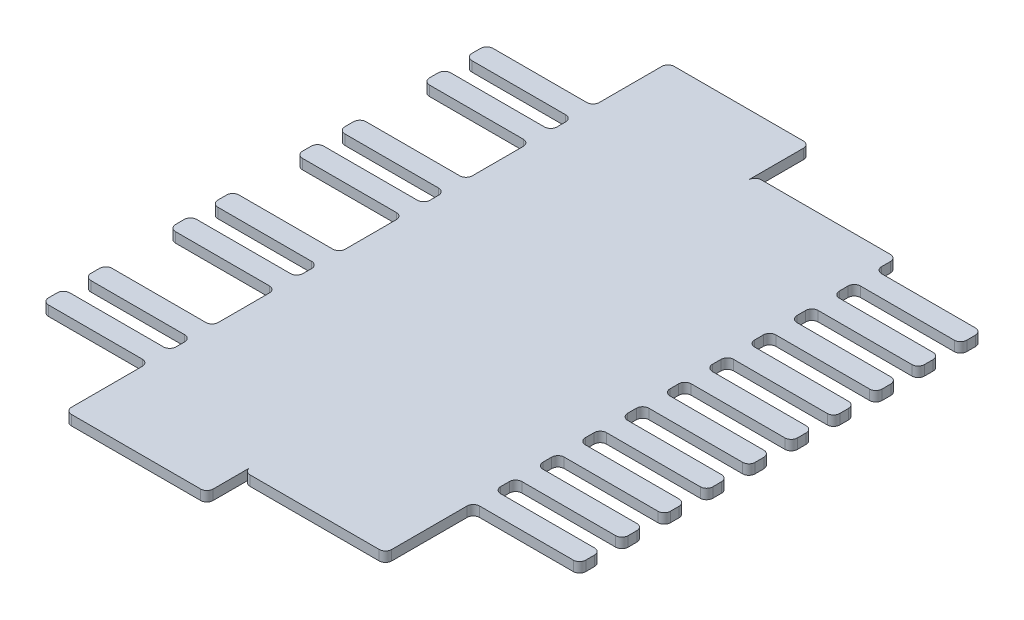
SolidWorks part; units mm, degrees
ref_plane "Front Plane" through (0, 0, 0) normal (0, 0, 1) x (1, 0, 0)
ref_plane "Top Plane" through (0, 0, 0) normal (0, 1, 0) x (1, 0, 0)
ref_plane "Right Plane" through (0, 0, 0) normal (1, 0, 0) x (0, 0, -1)
sketch "Sketch1" plane through (0, 0, 0) normal (0, 1, 0) x (1, 0, 0)
  line L0 (-0.75, 10) -> (-12, 10)
  line L2 (0, 9.25) -> (0, 0.75)
  line L5 (-12.75, 11.27) -> (0, 11.27) construction
  line L7 (-12.75, 10.75) -> (-12.75, 11.79)
  line L8 (-12, 12.54) -> (-0.75, 12.54)
  line L12 (0, 14.33) -> (0, 13.29)
  line L17 (-0.75, 15.08) -> (-12, 15.08)
  line L22 (-12.75, 15.83) -> (-12.75, 16.87)
  line L27 (-12, 17.62) -> (-0.75, 17.62)
  line L56 (16.25, 0) -> (0.75, 0)
  line L84 (0, 19.41) -> (0, 10.91) [skipped]
  line L85 (-0.75, 20.16) -> (-12, 20.16) [skipped]
  line L86 (-12.75, 20.91) -> (-12.75, 21.95) [skipped]
  line L87 (-12, 22.7) -> (-0.75, 22.7) [skipped]
  line L88 (0, 24.49) -> (0, 15.99) [skipped]
  line L89 (-0.75, 25.24) -> (-12, 25.24) [skipped]
  line L90 (-12.75, 25.99) -> (-12.75, 27.03) [skipped]
  line L91 (-12, 27.78) -> (-0.75, 27.78) [skipped]
  line L92 (0, 29.57) -> (0, 21.07) [skipped]
  line L93 (-0.75, 30.32) -> (-12, 30.32) [skipped]
  line L94 (-12.75, 31.07) -> (-12.75, 32.11) [skipped]
  line L95 (-12, 32.86) -> (-0.75, 32.86) [skipped]
  line L96 (0, 34.65) -> (0, 26.15) [skipped]
  line L97 (-0.75, 35.4) -> (-12, 35.4) [skipped]
  line L98 (-12.75, 36.15) -> (-12.75, 37.19) [skipped]
  line L99 (-12, 37.94) -> (-0.75, 37.94) [skipped]
  line L100 (0, 39.73) -> (0, 31.23) [skipped]
  line L101 (-0.75, 40.48) -> (-12, 40.48) [skipped]
  line L102 (-12.75, 41.23) -> (-12.75, 42.27) [skipped]
  line L103 (-12, 43.02) -> (-0.75, 43.02) [skipped]
  line L104 (0, 44.81) -> (0, 36.31) [skipped]
  line L105 (-0.75, 45.56) -> (-12, 45.56) [skipped]
  line L106 (-12.75, 46.31) -> (-12.75, 47.35) [skipped]
  line L107 (-12, 48.1) -> (-0.75, 48.1) [skipped]
  line L108 (0, 49.89) -> (0, 41.39) [skipped]
  line L109 (-0.75, 50.64) -> (-12, 50.64) [skipped]
  line L110 (-12.75, 51.39) -> (-12.75, 52.43) [skipped]
  line L111 (-12, 53.18) -> (-0.75, 53.18) [skipped]
  line L112 (0, 54.97) -> (0, 46.47) [skipped]
  line L113 (-0.75, 55.72) -> (-12, 55.72) [skipped]
  line L114 (-12.75, 56.47) -> (-12.75, 57.51) [skipped]
  line L115 (-12, 58.26) -> (-0.75, 58.26) [skipped]
  line L116 (-0.75, 25.24) -> (-12, 25.24)
  line L117 (-12.75, 25.99) -> (-12.75, 27.03)
  line L118 (-12, 27.78) -> (-0.75, 27.78)
  line L119 (0, 29.57) -> (0, 28.53)
  line L120 (-0.75, 30.32) -> (-12, 30.32)
  line L121 (-12.75, 31.07) -> (-12.75, 32.11)
  line L122 (-12, 32.86) -> (-0.75, 32.86)
  line L123 (-0.75, 40.48) -> (-12, 40.48)
  line L124 (-12.75, 41.23) -> (-12.75, 42.27)
  line L125 (-12, 43.02) -> (-0.75, 43.02)
  line L126 (0, 44.81) -> (0, 43.77)
  line L127 (-0.75, 45.56) -> (-12, 45.56)
  line L128 (-12.75, 46.31) -> (-12.75, 47.35)
  line L129 (-12, 48.1) -> (-0.75, 48.1)
  line L130 (-0.75, 55.72) -> (-12, 55.72)
  line L131 (-12.75, 56.47) -> (-12.75, 57.51)
  line L132 (-12, 58.26) -> (-0.75, 58.26)
  line L133 (0, 60.05) -> (0, 59.01)
  line L134 (-0.75, 60.8) -> (-12, 60.8)
  line L135 (-12.75, 61.55) -> (-12.75, 62.59)
  line L136 (-12, 63.34) -> (-0.75, 63.34)
  line L137 (0, 24.49) -> (0, 18.37)
  line L138 (0, 33.61) -> (0, 39.73)
  line L139 (0, 48.85) -> (0, 54.97)
  line L140 (0, 64.09) -> (0, 71.59)
  line L141 (0.75, 72.34) -> (16.25, 72.34)
  line L142 (17, 71.59) -> (17, 65.023)
  line L143 (34.75, 63.233) -> (46, 63.233)
  line L144 (34, 63.983) -> (34, 65.023)
  line L145 (46.75, 61.963) -> (34, 61.963) construction
  line L146 (46.75, 62.483) -> (46.75, 61.443)
  line L147 (46, 60.693) -> (34.75, 60.693)
  line L148 (34, 58.903) -> (34, 59.943)
  line L149 (34.75, 58.153) -> (46, 58.153)
  line L150 (46.75, 57.403) -> (46.75, 56.363)
  line L151 (46, 55.613) -> (34.75, 55.613)
  line L152 (34, 53.823) -> (34, 54.863)
  line L153 (34.75, 53.073) -> (46, 53.073)
  line L154 (46.75, 52.323) -> (46.75, 51.283)
  line L155 (46, 50.533) -> (34.75, 50.533)
  line L156 (34, 48.743) -> (34, 49.783)
  line L157 (34, 14.223) -> (34, 5.183)
  line L158 (33.25, 4.433) -> (17.75, 4.433)
  line L159 (17, 5.183) -> (17, 65.023) construction
  line L160 (17.75, 65.773) -> (33.25, 65.773)
  line L161 (34.75, 47.993) -> (46, 47.993)
  line L162 (46.75, 47.243) -> (46.75, 46.203)
  line L163 (46, 45.453) -> (34.75, 45.453)
  line L164 (34, 43.663) -> (34, 44.703)
  line L165 (34.75, 42.913) -> (46, 42.913)
  line L166 (46.75, 42.163) -> (46.75, 41.123)
  line L167 (46, 40.373) -> (34.75, 40.373)
  line L168 (34, 38.583) -> (34, 39.623)
  line L169 (34.75, 37.833) -> (46, 37.833)
  line L170 (46.75, 37.083) -> (46.75, 36.043)
  line L171 (46, 35.293) -> (34.75, 35.293)
  line L172 (34, 33.503) -> (34, 34.543)
  line L173 (34.75, 32.753) -> (46, 32.753)
  line L174 (46.75, 32.003) -> (46.75, 30.963)
  line L175 (46, 30.213) -> (34.75, 30.213)
  line L176 (34, 28.423) -> (34, 29.463)
  line L177 (34.75, 27.673) -> (46, 27.673)
  line L178 (46.75, 26.923) -> (46.75, 25.883)
  line L179 (46, 25.133) -> (34.75, 25.133)
  line L180 (34, 23.343) -> (34, 24.383)
  line L181 (34.75, 22.593) -> (46, 22.593)
  line L182 (46.75, 21.843) -> (46.75, 20.803)
  line L183 (46, 20.053) -> (34.75, 20.053)
  line L184 (34, 18.263) -> (34, 19.303)
  line L185 (34.75, 17.513) -> (46, 17.513)
  line L186 (46.75, 16.763) -> (46.75, 15.723)
  line L187 (46, 14.973) -> (34.75, 14.973)
  line L188 (17, 65.023) -> (17, 5.183) construction
  line L189 (17, 5.183) -> (17, 0.75)
  arc A0 (-0.75, 12.54) -> (0, 13.29) centre (-0.75, 13.29) ccw
  arc A1 (-12.75, 11.79) -> (-12, 12.54) centre (-12, 11.79) cw
  arc A2 (-12, 10) -> (-12.75, 10.75) centre (-12, 10.75) cw
  arc A3 (0, 0.75) -> (0.75, 0) centre (0.75, 0.75) ccw
  arc A4 (-0.75, 10) -> (0, 9.25) centre (-0.75, 9.25) cw
  arc A5 (17, 0.75) -> (16.25, 0) centre (16.25, 0.75) cw
  arc A6 (-0.75, 15.08) -> (0, 14.33) centre (-0.75, 14.33) cw
  arc A7 (-12, 15.08) -> (-12.75, 15.83) centre (-12, 15.83) cw
  arc A8 (-12.75, 16.87) -> (-12, 17.62) centre (-12, 16.87) cw
  arc A9 (-0.75, 17.62) -> (0, 18.37) centre (-0.75, 18.37) ccw
  arc A44 (-0.75, 20.16) -> (0, 19.41) centre (-0.75, 19.41) cw [skipped]
  arc A45 (-12, 20.16) -> (-12.75, 20.91) centre (-12, 20.91) cw [skipped]
  arc A46 (-12.75, 21.95) -> (-12, 22.7) centre (-12, 21.95) cw [skipped]
  arc A47 (-0.75, 22.7) -> (0, 23.45) centre (-0.75, 23.45) ccw [skipped]
  arc A48 (-0.75, 25.24) -> (0, 24.49) centre (-0.75, 24.49) cw [skipped]
  arc A49 (-12, 25.24) -> (-12.75, 25.99) centre (-12, 25.99) cw [skipped]
  arc A50 (-12.75, 27.03) -> (-12, 27.78) centre (-12, 27.03) cw [skipped]
  arc A51 (-0.75, 27.78) -> (0, 28.53) centre (-0.75, 28.53) ccw [skipped]
  arc A52 (-0.75, 30.32) -> (0, 29.57) centre (-0.75, 29.57) cw [skipped]
  arc A53 (-12, 30.32) -> (-12.75, 31.07) centre (-12, 31.07) cw [skipped]
  arc A54 (-12.75, 32.11) -> (-12, 32.86) centre (-12, 32.11) cw [skipped]
  arc A55 (-0.75, 32.86) -> (0, 33.61) centre (-0.75, 33.61) ccw [skipped]
  arc A56 (-0.75, 35.4) -> (0, 34.65) centre (-0.75, 34.65) cw [skipped]
  arc A57 (-12, 35.4) -> (-12.75, 36.15) centre (-12, 36.15) cw [skipped]
  arc A58 (-12.75, 37.19) -> (-12, 37.94) centre (-12, 37.19) cw [skipped]
  arc A59 (-0.75, 37.94) -> (0, 38.69) centre (-0.75, 38.69) ccw [skipped]
  arc A60 (-0.75, 40.48) -> (0, 39.73) centre (-0.75, 39.73) cw [skipped]
  arc A61 (-12, 40.48) -> (-12.75, 41.23) centre (-12, 41.23) cw [skipped]
  arc A62 (-12.75, 42.27) -> (-12, 43.02) centre (-12, 42.27) cw [skipped]
  arc A63 (-0.75, 43.02) -> (0, 43.77) centre (-0.75, 43.77) ccw [skipped]
  arc A64 (-0.75, 45.56) -> (0, 44.81) centre (-0.75, 44.81) cw [skipped]
  arc A65 (-12, 45.56) -> (-12.75, 46.31) centre (-12, 46.31) cw [skipped]
  arc A66 (-12.75, 47.35) -> (-12, 48.1) centre (-12, 47.35) cw [skipped]
  arc A67 (-0.75, 48.1) -> (0, 48.85) centre (-0.75, 48.85) ccw [skipped]
  arc A68 (-0.75, 50.64) -> (0, 49.89) centre (-0.75, 49.89) cw [skipped]
  arc A69 (-12, 50.64) -> (-12.75, 51.39) centre (-12, 51.39) cw [skipped]
  arc A70 (-12.75, 52.43) -> (-12, 53.18) centre (-12, 52.43) cw [skipped]
  arc A71 (-0.75, 53.18) -> (0, 53.93) centre (-0.75, 53.93) ccw [skipped]
  arc A72 (-0.75, 55.72) -> (0, 54.97) centre (-0.75, 54.97) cw [skipped]
  arc A73 (-12, 55.72) -> (-12.75, 56.47) centre (-12, 56.47) cw [skipped]
  arc A74 (-12.75, 57.51) -> (-12, 58.26) centre (-12, 57.51) cw [skipped]
  arc A75 (-0.75, 58.26) -> (0, 59.01) centre (-0.75, 59.01) ccw [skipped]
  arc A76 (-0.75, 27.78) -> (0, 28.53) centre (-0.75, 28.53) ccw
  arc A77 (-12.75, 27.03) -> (-12, 27.78) centre (-12, 27.03) cw
  arc A78 (-12, 25.24) -> (-12.75, 25.99) centre (-12, 25.99) cw
  arc A79 (-0.75, 25.24) -> (0, 24.49) centre (-0.75, 24.49) cw
  arc A80 (-0.75, 30.32) -> (0, 29.57) centre (-0.75, 29.57) cw
  arc A81 (-12, 30.32) -> (-12.75, 31.07) centre (-12, 31.07) cw
  arc A82 (-12.75, 32.11) -> (-12, 32.86) centre (-12, 32.11) cw
  arc A83 (-0.75, 32.86) -> (0, 33.61) centre (-0.75, 33.61) ccw
  arc A84 (-0.75, 43.02) -> (0, 43.77) centre (-0.75, 43.77) ccw
  arc A85 (-12.75, 42.27) -> (-12, 43.02) centre (-12, 42.27) cw
  arc A86 (-12, 40.48) -> (-12.75, 41.23) centre (-12, 41.23) cw
  arc A87 (-0.75, 40.48) -> (0, 39.73) centre (-0.75, 39.73) cw
  arc A88 (-0.75, 45.56) -> (0, 44.81) centre (-0.75, 44.81) cw
  arc A89 (-12, 45.56) -> (-12.75, 46.31) centre (-12, 46.31) cw
  arc A90 (-12.75, 47.35) -> (-12, 48.1) centre (-12, 47.35) cw
  arc A91 (-0.75, 48.1) -> (0, 48.85) centre (-0.75, 48.85) ccw
  arc A92 (-0.75, 58.26) -> (0, 59.01) centre (-0.75, 59.01) ccw
  arc A93 (-12.75, 57.51) -> (-12, 58.26) centre (-12, 57.51) cw
  arc A94 (-12, 55.72) -> (-12.75, 56.47) centre (-12, 56.47) cw
  arc A95 (-0.75, 55.72) -> (0, 54.97) centre (-0.75, 54.97) cw
  arc A96 (-0.75, 60.8) -> (0, 60.05) centre (-0.75, 60.05) cw
  arc A97 (-12, 60.8) -> (-12.75, 61.55) centre (-12, 61.55) cw
  arc A98 (-12.75, 62.59) -> (-12, 63.34) centre (-12, 62.59) cw
  arc A99 (-0.75, 63.34) -> (0, 64.09) centre (-0.75, 64.09) ccw
  arc A100 (0, 71.59) -> (0.75, 72.34) centre (0.75, 71.59) cw
  arc A101 (16.25, 72.34) -> (17, 71.59) centre (16.25, 71.59) cw
  arc A102 (34.75, 60.693) -> (34, 59.943) centre (34.75, 59.943) ccw
  arc A103 (46.75, 61.443) -> (46, 60.693) centre (46, 61.443) cw
  arc A104 (46, 63.233) -> (46.75, 62.483) centre (46, 62.483) cw
  arc A105 (34, 65.023) -> (33.25, 65.773) centre (33.25, 65.023) ccw
  arc A106 (34.75, 63.233) -> (34, 63.983) centre (34.75, 63.983) cw
  arc A107 (17, 65.023) -> (17.75, 65.773) centre (17.75, 65.023) cw
  arc A108 (34.75, 58.153) -> (34, 58.903) centre (34.75, 58.903) cw
  arc A109 (46, 58.153) -> (46.75, 57.403) centre (46, 57.403) cw
  arc A110 (46.75, 56.363) -> (46, 55.613) centre (46, 56.363) cw
  arc A111 (34.75, 55.613) -> (34, 54.863) centre (34.75, 54.863) ccw
  arc A112 (34.75, 53.073) -> (34, 53.823) centre (34.75, 53.823) cw
  arc A113 (46, 53.073) -> (46.75, 52.323) centre (46, 52.323) cw
  arc A114 (46.75, 51.283) -> (46, 50.533) centre (46, 51.283) cw
  arc A115 (34.75, 50.533) -> (34, 49.783) centre (34.75, 49.783) ccw
  arc A116 (34.75, 47.993) -> (34, 48.743) centre (34.75, 48.743) cw
  arc A117 (46, 47.993) -> (46.75, 47.243) centre (46, 47.243) cw
  arc A118 (46.75, 46.203) -> (46, 45.453) centre (46, 46.203) cw
  arc A119 (34.75, 45.453) -> (34, 44.703) centre (34.75, 44.703) ccw
  arc A120 (34.75, 42.913) -> (34, 43.663) centre (34.75, 43.663) cw
  arc A121 (46, 42.913) -> (46.75, 42.163) centre (46, 42.163) cw
  arc A122 (46.75, 41.123) -> (46, 40.373) centre (46, 41.123) cw
  arc A123 (34.75, 40.373) -> (34, 39.623) centre (34.75, 39.623) ccw
  arc A124 (34.75, 37.833) -> (34, 38.583) centre (34.75, 38.583) cw
  arc A125 (46, 37.833) -> (46.75, 37.083) centre (46, 37.083) cw
  arc A126 (46.75, 36.043) -> (46, 35.293) centre (46, 36.043) cw
  arc A127 (34.75, 35.293) -> (34, 34.543) centre (34.75, 34.543) ccw
  arc A128 (34.75, 32.753) -> (34, 33.503) centre (34.75, 33.503) cw
  arc A129 (46, 32.753) -> (46.75, 32.003) centre (46, 32.003) cw
  arc A130 (46.75, 30.963) -> (46, 30.213) centre (46, 30.963) cw
  arc A131 (34.75, 30.213) -> (34, 29.463) centre (34.75, 29.463) ccw
  arc A132 (34.75, 27.673) -> (34, 28.423) centre (34.75, 28.423) cw
  arc A133 (46, 27.673) -> (46.75, 26.923) centre (46, 26.923) cw
  arc A134 (46.75, 25.883) -> (46, 25.133) centre (46, 25.883) cw
  arc A135 (34.75, 25.133) -> (34, 24.383) centre (34.75, 24.383) ccw
  arc A136 (34.75, 22.593) -> (34, 23.343) centre (34.75, 23.343) cw
  arc A137 (46, 22.593) -> (46.75, 21.843) centre (46, 21.843) cw
  arc A138 (46.75, 20.803) -> (46, 20.053) centre (46, 20.803) cw
  arc A139 (34.75, 20.053) -> (34, 19.303) centre (34.75, 19.303) ccw
  arc A140 (34.75, 17.513) -> (34, 18.263) centre (34.75, 18.263) cw
  arc A141 (46, 17.513) -> (46.75, 16.763) centre (46, 16.763) cw
  arc A142 (46.75, 15.723) -> (46, 14.973) centre (46, 15.723) cw
  arc A143 (34.75, 14.973) -> (34, 14.223) centre (34.75, 14.223) ccw
  arc A144 (34, 5.183) -> (33.25, 4.433) centre (33.25, 5.183) cw
  arc A145 (17.75, 4.433) -> (17, 5.183) centre (17.75, 5.183) cw
  point P0 (0, 0)
  point P27 (34, 65.773)
  point P48 (-12.75, 12.54)
  point P69 (-12.75, 10)
  point P78 (0, 0)
  point P81 (0, 10)
  point P123 (-6.375, 63.34)
  point P140 (34, 60.693)
  dimension "D6" = 0.75
  dimension "D7" = 0.75
  dimension "D8" = 4
  dimension "D9" = 10.16
  dimension "D11" = 0.75
  dimension "D13" = 0.75
  dimension "D14" = 0.75
  dimension "D15" = 0.75
  dimension "D16" = 0.75
  dimension "D1" = 2.54
  dimension "D2" = 12
  dimension "D3" = 10
  dimension "D4" = 10
  dimension "D5" = 17
  dimension "D10" = 5.08
  dimension "D12" = 9
  dimension "D17" = 5.08
  dimension "D18" = 12
  dimension "D19" = 10.54
extrude "Boss-Extrude1" add sketch "Sketch1" along normal blind 1.2
